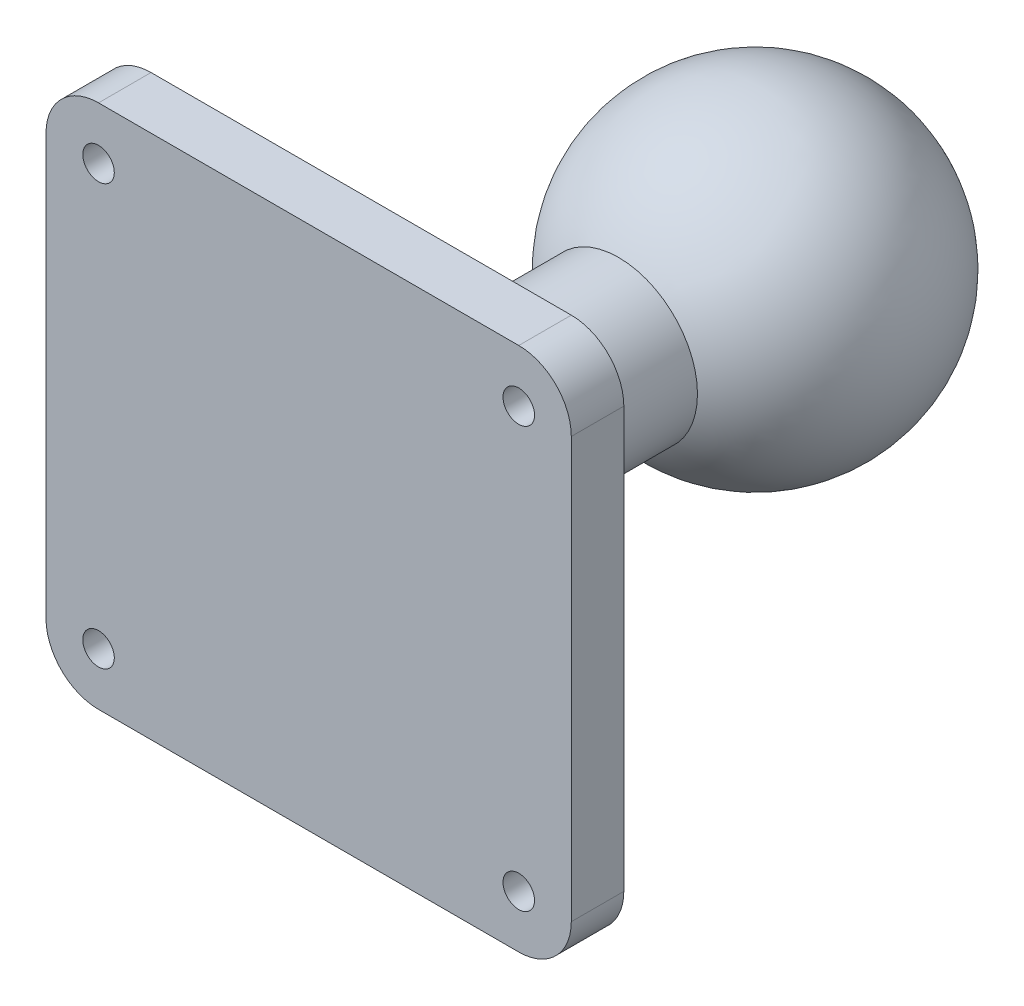
SolidWorks part; units mm, degrees
ref_plane "Alzado" through (0, 0, 0) normal (0, 0, 1) x (1, 0, 0)
ref_plane "Planta" through (0, 0, 0) normal (0, 1, 0) x (1, 0, 0)
ref_plane "Vista lateral" through (0, 0, 0) normal (1, 0, 0) x (0, 0, -1)
sketch "Croquis1" plane through (0, 0, 0) normal (0, 0, 1) x (1, 0, 0)
  line L1 (-25, -25) -> (25, -25)
  line L2 (-25, -25) -> (-25, 25)
  line L3 (-25, 25) -> (25, 25)
  line L4 (25, -25) -> (25, 25)
  line L5 (-25, -25) -> (25, 25) construction
  line L6 (-25, 25) -> (25, -25) construction
  point P0 (0, 0)
  dimension "D1" = 50
  dimension "D2" = 50
extrude "Saliente-Extruir1" add sketch "Croquis1" along normal blind 5
sketch "Croquis2" plane through (0, 0, 0) normal (0, 0, -1) x (-1, 0, 0)
  circle A0 centre (0, 0) radius 7.5
  dimension "D1" = 15
ref_plane "Plano1" through (0, 0, -37.5) normal (0, 0, -1) x (-1, 0, 0)
sketch "Croquis3" plane through (0, 0, -37.5) normal (0, 0, -1) x (-1, 0, 0)
  line L0 (0, 15) -> (0, -15) construction
  line L1 (0, 15) -> (0, -15)
  arc A0 (0, -15) -> (0, 15) centre (0, 0) ccw
  dimension "D1" = 30
revolve "Revolución1" add sketch "Croquis3" angle 360 about L0
extrude "Saliente-Extruir2" add sketch "Croquis2" along normal up to surface (24.5096 mm away) contours A0
sketch "Croquis4" plane through (0, 0, 0) normal (0, 0, -1) x (-1, 0, 0)
  line L0 (-25, 25) -> (25, 25) construction
  line L1 (-25, -25) -> (-25, 25) construction
  line L2 (0, 25) -> (0, 0) construction
  line L3 (0, 0) -> (25, 0) construction
  line L4 (25, 25) -> (25, -25) construction
  circle A0 centre (-20, 20) radius 1.5
  circle A1 centre (20, 20) radius 1.5
  circle A2 centre (20, -20) radius 1.5
  circle A3 centre (-20, -20) radius 1.5
  dimension "D1" = 3
  dimension "D2" = 5
  dimension "D3" = 5
extrude "Cortar-Extruir1" cut sketch "Croquis4" against normal blind 5
fillet "Redondeo1" radius 5 4 edges at (25, -25, 2.5) (-25, -25, 2.5) (-25, 25, 2.5) (25, 25, 2.5)
fillet "Redondeo2" radius 5 1 edges at (-7.5, 0, 0)
